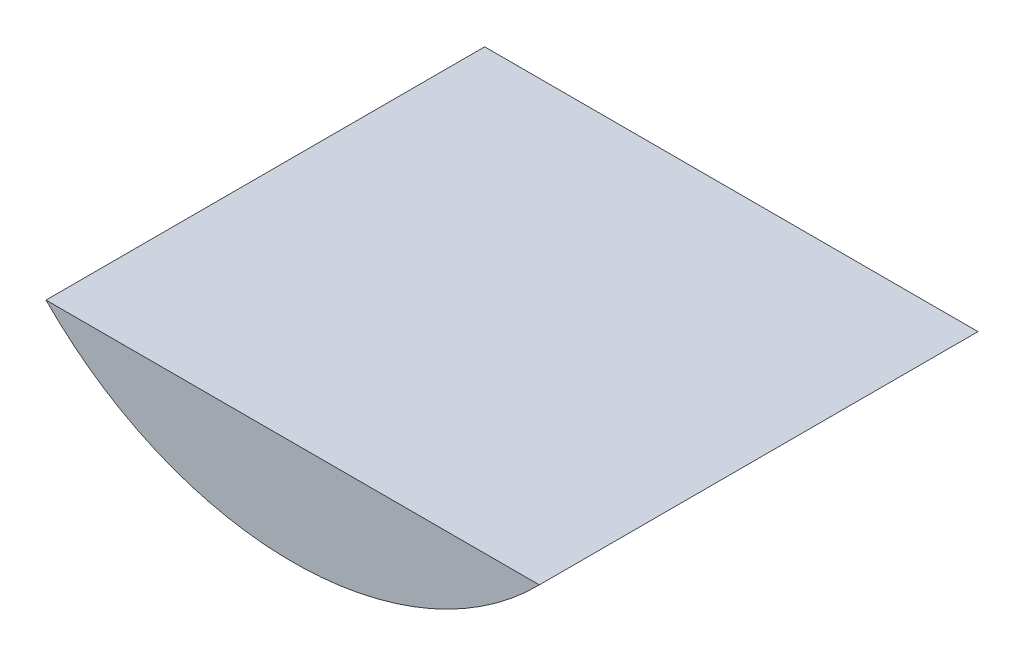
SolidWorks part; units mm, degrees
ref_plane "Front Plane" through (0, 0, 0) normal (0, 0, 1) x (1, 0, 0)
ref_plane "Top Plane" through (0, 0, 0) normal (0, 1, 0) x (1, 0, 0)
ref_plane "Right Plane" through (0, 0, 0) normal (1, 0, 0) x (0, 0, -1)
sketch "Sketch2" plane through (0, 0, 0) normal (0, 0, 1) x (1, 0, 0)
  line L0 (-71.4143, -70) -> (71.4143, -70)
  arc A0 (-71.4143, -70) -> (71.4143, -70) centre (0, 0) ccw
  point P5 (0, -70)
  point P6 (0, -100)
  dimension "D1" = 200
  dimension "D2" = 30
extrude "Boss-Extrude1" add sketch "Sketch2" along normal blind 127
